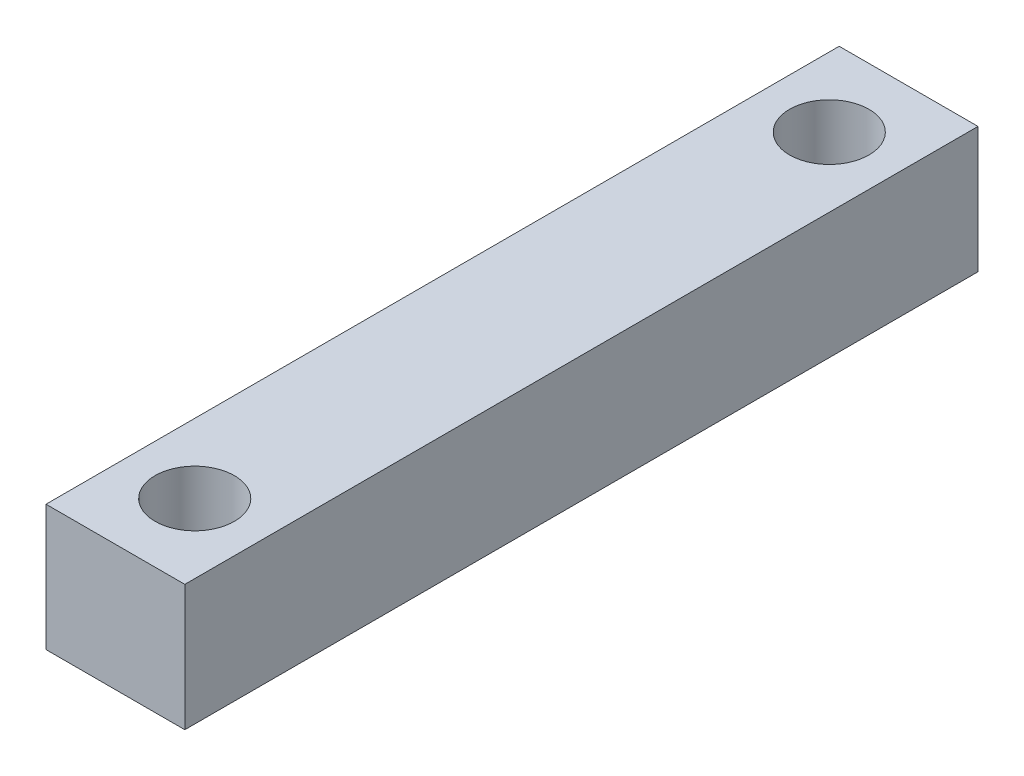
SolidWorks part; units mm, degrees
ref_plane "Front Plane" through (0, 0, 0) normal (0, 0, 1) x (1, 0, 0)
ref_plane "Top Plane" through (0, 0, 0) normal (0, 1, 0) x (1, 0, 0)
ref_plane "Right Plane" through (0, 0, 0) normal (1, 0, 0) x (0, 0, -1)
sketch "Sketch1" plane through (0, 0, 0) normal (0, 1, 0) x (1, 0, 0)
  line L1 (-3.5, 20) -> (3.5, 20)
  line L2 (-3.5, 20) -> (-3.5, -20)
  line L3 (-3.5, -20) -> (3.5, -20)
  line L4 (3.5, 20) -> (3.5, -20)
  line L5 (-3.5, 20) -> (3.5, -20) construction
  line L6 (-3.5, -20) -> (3.5, 20) construction
  point P0 (0, 0)
  dimension "D1" = 40
  dimension "D2" = 7
extrude "Boss-Extrude1" add sketch "Sketch1" along normal blind 3.175
sketch "Sketch2" plane through (0, 3.175, 0) normal (0, 1, 0) x (1, 0, 0)
  line L0 (0, 20) -> (0, -20) construction
  line L1 (3.5, 20) -> (-3.5, 20) construction
  line L2 (-3.5, -20) -> (3.5, -20) construction
  line L3 (-3.5, 0) -> (3.5, 0) construction
  line L4 (-3.5, 20) -> (3.5, 20)
  line L5 (-3.5, 20) -> (-3.5, -20)
  line L6 (-3.5, -20) -> (3.5, -20)
  line L7 (3.5, 20) -> (3.5, -20)
  circle A0 centre (0, 16) radius 2
  circle A1 centre (0, -16) radius 2
  dimension "D1" = 4
  dimension "D2" = 32
  dimension "D3" = 16
extrude "Boss-Extrude2" add sketch "Sketch2" along normal blind 3.175
